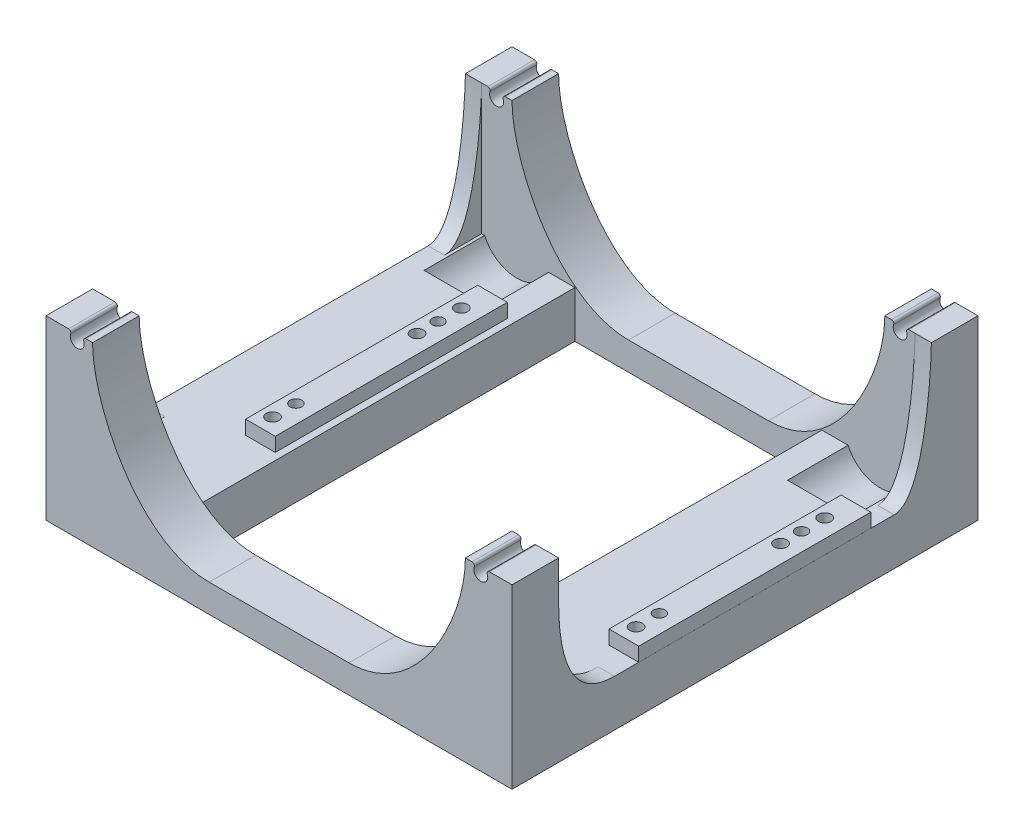
SolidWorks part; units mm, degrees
other "标注1"
sketch "草图19" plane through (-50, 38.0005, 50) normal (-0.1688, 0.677, 0.7163) x (0.9244, -0.1433, 0.3534)
ref_plane "前视基准面" through (0, 0, 0) normal (0, 0, 1) x (1, 0, 0)
ref_plane "上视基准面" through (0, 0, 0) normal (0, 1, 0) x (1, 0, 0)
ref_plane "右视基准面" through (0, 0, 0) normal (1, 0, 0) x (0, 0, -1)
sketch "草图1" plane through (0, 0, 0) normal (0, 1, 0) x (1, 0, 0)
  line L1 (-50, 50) -> (50, 50)
  line L2 (-50, 50) -> (-50, -50)
  line L3 (-50, -50) -> (50, -50)
  line L4 (50, 50) -> (50, -50)
  line L5 (-50, 50) -> (50, -50) construction
  line L6 (-50, -50) -> (50, 50) construction
  point P0 (0, 0)
  dimension "D1" = 100
  dimension "D2" = 100
extrude "凸台-拉伸1" add sketch "草图1" along normal blind 3
sketch "草图2" plane through (0, 3, 0) normal (0, 1, 0) x (1, 0, 0)
  line L1 (0, 0) -> (0, 7.7129) construction
  line L2 (0, 0) -> (13.0975, 0) construction
  line L3 (40, 50) -> (40, 40)
  line L4 (-50, 50) -> (-40, 50)
  line L5 (-50, 50) -> (-50, 40)
  line L6 (-50, 40) -> (-40, 40)
  line L7 (-40, 50) -> (-40, 40)
  line L8 (50, 40) -> (40, 40)
  line L9 (50, 50) -> (50, 40)
  line L10 (50, 50) -> (40, 50)
  line L11 (50, -50) -> (40, -50)
  line L12 (50, -50) -> (50, -40)
  line L13 (50, -40) -> (40, -40)
  line L14 (-40, -50) -> (-40, -40)
  line L15 (-50, -40) -> (-40, -40)
  line L16 (-50, -50) -> (-50, -40)
  line L17 (-50, -50) -> (-40, -50)
  line L18 (40, -50) -> (40, -40)
  dimension "D2" = 10
  dimension "D3" = 10
extrude "凸台-拉伸2" add sketch "草图2" along normal blind 35
sketch "草图4" plane through (0, 38, 0) normal (0, 1, 0) x (1, 0, 0)
  line L0 (0, 0) -> (0, 4.7168) construction
  line L1 (0, 0) -> (6.2704, 0) construction
  line L2 (-43.3, 45) -> (43.3, 45)
  line L3 (-40, 40) -> (-40, 50) construction
  point P3 (0, 45)
  point P9 (-40, 45)
  dimension "D1" = 86.6
sketch "草图5" plane through (0, 0, -50) normal (0, 0, -1) x (-1, 0, 0)
  line L0 (-43.3, 36.8) -> (43.3, 36.8) construction
  line L1 (0, 0) -> (0, 16.0032) construction
  line L2 (-50, 38) -> (-40, 38) construction
  circle A0 centre (-43.3, 36.8) radius 1.5
  circle A1 centre (43.3, 36.8) radius 1.5
  point P5 (0, 36.8)
  dimension "D2" = 3
  dimension "D1" = 86.6
  dimension "D3" = 1.2
extrude "切除-拉伸2" cut sketch "草图5" against normal up to surface (100 mm away) contours A1 | A0
fillet "圆角1" radius 0.5 8 edges at (-44.2, 38, 45) (-42.4, 38, 45) (44.2, 38, 45) (42.4, 38, 45) (44.2, 38, -45) (42.4, 38, -45) (-44.2, 38, -45) (-42.4, 38, -45)
sketch "草图7" plane through (0, 3, 0) normal (0, 1, 0) x (1, 0, 0)
  line L1 (-40, 50) -> (40, 50)
  line L2 (-40, 50) -> (-40, 40)
  line L3 (-40, 40) -> (40, 40)
  line L4 (40, 50) -> (40, 40)
  line L5 (-40, -40) -> (40, -40)
  line L6 (-40, -40) -> (-40, -50)
  line L7 (-40, -50) -> (40, -50)
  line L8 (40, -40) -> (40, -50)
  line M2 (-40, -40) -> (-40, -50)
  line M3 (-40, -50) -> (40, -50)
  line M4 (40, -50) -> (40, -40)
  line M8 (40, 40) -> (40, 50)
  line M9 (40, 50) -> (-40, 50)
  line M10 (-40, 50) -> (-40, 40)
extrude "凸台-拉伸3" add sketch "草图7" along normal blind 3 contours L5 M2 M3 M4 | L3 M10 M8 M9
sketch "草图8" plane through (0, 0, 50) normal (0, 0, 1) x (1, 0, 0)
  line L1 (-40, 38) -> (-40, 6) construction
  line L2 (0, 0) -> (0, 19.6517) construction
  line L3 (-50, 0) -> (50, 0) construction
  line L4 (-40, 38) -> (-40, 6)
  line L5 (-40, 6) -> (-15, 6)
  line L6 (40, 6) -> (15, 6)
  line L7 (40, 38) -> (40, 6)
  line L8 (-40, 6) -> (40, 6) construction
  spline S0 degree 3 poles (-40, 38) (-40, 26.4936) (-30.1503, 6) (-15, 6) knots 0 0 0 0 1 1 1 1
  spline S1 degree 3 poles (40, 38) (40, 26.4936) (30.1503, 6) (15, 6) knots 0 0 0 0 1 1 1 1
  dimension "D1" = 25
extrude "凸台-拉伸4" add sketch "草图8" against normal up to surface (10 mm away) up to face at (0, 29.2338, 40)
sketch "草图9" plane through (0, 0, -50) normal (0, 0, -1) x (-1, 0, 0)
  line L2 (-40, 6) -> (-15, 6)
  line L3 (-40, 38) -> (-40, 6)
  line L4 (-40, 6) -> (-15, 6)
  line L5 (-40, 38) -> (-40, 6)
  line L6 (40, 6) -> (40, 38)
  line L7 (15, 6) -> (40, 6)
  line L8 (40, 6) -> (40, 38)
  line L9 (15, 6) -> (40, 6)
  spline S1 degree 3 poles (144.0222, 1994.8743) (169.4851, -2146.6398) (-527.9806, 2160.2859) (637.2814, -1841.186) knots -3.481249 -3.481249 -3.481249 -3.481249 4.802323 4.802323 4.802323 4.802323 only from (-15, 6) to (-40, 38)
  spline S2 degree 3 poles (-15, 6) (-30.1503, 6) (-40, 26.4936) (-40, 38) knots 0 0 0 0 1 1 1 1
  spline S3 degree 3 poles (-637.2972, -1841.2401) (527.993, 2160.3455) (-169.4925, -2146.7034) (-144.0219, 1994.9391) knots -3.80236 -3.80236 -3.80236 -3.80236 4.481293 4.481293 4.481293 4.481293 only from (40, 38) to (15, 6)
  spline S4 degree 3 poles (40, 38) (40, 26.4936) (30.1503, 6) (15, 6) knots 0 0 0 0 1 1 1 1
  dimension "D1" = 0
  dimension "D2" = 0
extrude "凸台-拉伸5" add sketch "草图9" against normal up to surface (10 mm away) up to face at (0, 29.2338, -40)
sketch "草图13" plane through (0, 3, 0) normal (0, 1, 0) x (1, 0, 0)
  line L0 (-15, -40) -> (-40, -40) construction
  line L1 (-50, 40) -> (-26.5, 40)
  line L2 (-50, 40) -> (-50, -40)
  line L3 (-50, -40) -> (-26.5, -40)
  line L4 (-26.5, 40) -> (-26.5, -40)
  line L5 (0, 0) -> (0, 12.4969) construction
  line L6 (26.5, 40) -> (26.5, -40)
  line L7 (50, -40) -> (26.5, -40)
  line L8 (50, 40) -> (50, -40)
  line L9 (50, 40) -> (26.5, 40)
  dimension "D1" = 23.5
extrude "凸台-拉伸6" add sketch "草图13" along normal blind 7
sketch "草图17" plane through (50, 0, 0) normal (1, 0, 0) x (0, 0, -1)
  line L0 (-40, 10) -> (40, 10) construction
  line L1 (40, 38) -> (40, 10) construction
  line L2 (32, 10) -> (40, 10)
  line L3 (40, 10) -> (40, 38)
  line L4 (-40, 38) -> (-40, 10) construction
  line L6 (-40, 30) -> (-40, 10)
  line L7 (-40, 10) -> (-28, 10)
  spline S0 degree 3 poles (40, 38) (40, 35.1023) (38.9761, 10) (32, 10) knots 0 0 0 0 1 1 1 1
  spline S1 degree 2 poles (-40, 30) (-40, 10) (-28, 10) knots 0 0 0 1 1 1
  point P11 (37.8859, 23.9283)
  point P14 (37.9112, 24.8759)
  point P19 (0, 0)
  point P20 (38.8248, 24.2084)
  dimension "D1" = 8
  dimension "D2" = 12
  dimension "D3" = 20
extrude "凸台-拉伸8" add sketch "草图17" against normal blind 3.5
sketch "草图18" plane through (-50, 0, 0) normal (-1, 0, 0) x (0, 0, 1)
  line L2 (40, 10) -> (40, 30)
  line L3 (28, 10) -> (40, 10)
  line L4 (40, 10) -> (40, 30)
  line L5 (28, 10) -> (40, 10)
  line L6 (-40, 10) -> (-32, 10)
  line L7 (-40, 38) -> (-40, 10)
  line L8 (-40, 10) -> (-32, 10)
  line L9 (-40, 38) -> (-40, 10)
  parabola Q1 (40, 30) -> (28, 10) focus (31.1765, 15.2941) apex (33.5121, 11.4014)
  parabola Q2 (40, 30) -> (28, 10) focus (31.1765, 15.2941) apex (33.5121, 11.4014)
  spline S1 degree 3 poles (326.3572, 1976.9584) (-292.9927, -2127.0588) (132.3966, 2186.1852) (-155.4921, -1958.5179) knots -3.006877 -3.006877 -3.006877 -3.006877 4.085231 4.085231 4.085231 4.085231 only from (-32, 10) to (-40, 38)
  spline S2 degree 3 poles (-32, 10) (-38.9761, 10) (-40, 35.1023) (-40, 38) knots 0 0 0 0 1 1 1 1
  dimension "D1" = 0
  dimension "D2" = 0
extrude "凸台-拉伸9" add sketch "草图18" against normal blind 3.5
sketch "草图12" plane through (0, 0, -40) normal (0, 0, 1) x (1, 0, 0)
  line L0 (-50, 38) -> (-50, 0) construction
  line L3 (0, 0) -> (0, 12.4127) construction
  line L4 (-26.5, 10) -> (-46.5, 10) construction
  circle A0 centre (-39, 13) radius 7.5
  circle A1 centre (39, 13) radius 7.5
  dimension "D1" = 15
  dimension "D2" = 3
  dimension "D3" = 11
extrude "切除-拉伸3" cut sketch "草图12" along normal blind 13
sketch "草图14" plane through (0, 10, 0) normal (0, 1, 0) x (1, 0, 0)
  line L0 (-45.8739, 27) -> (-45.8739, 40) construction
  line L1 (-34.3739, 27) -> (-28.0039, 27)
  line L2 (-34.3739, 27) -> (-34.3739, -22.8)
  line L3 (-34.3739, -22.8) -> (-28.0039, -22.8)
  line L4 (-28.0039, 27) -> (-28.0039, -22.8)
  line L7 (-45.8739, 27) -> (-32.1261, 27) construction
  line L8 (0, 0) -> (0, 13.2318) construction
  line L9 (-31.8739, 27) -> (-31.8739, -22.8) construction
  line L10 (43.6261, 27) -> (49.9961, 27)
  line L11 (43.6261, 27) -> (43.6261, -22.8)
  line L12 (43.6261, -22.8) -> (49.9961, -22.8)
  line L13 (49.9961, 27) -> (49.9961, -22.8)
  line L14 (46.1261, 27) -> (46.1261, -22.8) construction
  circle A0 centre (-31.8739, 21) radius 1.35
  circle A1 centre (-31.8739, 16) radius 1.25
  circle A2 centre (-31.8739, 11.5) radius 1.35
  circle A3 centre (-31.8739, -14.5) radius 1.25
  circle A4 centre (-31.8739, -19.5) radius 1.35
  circle A5 centre (46.1261, 21) radius 1.35
  circle A6 centre (46.1261, 16) radius 1.25
  circle A7 centre (46.1261, 11.5) radius 1.35
  circle A8 centre (46.1261, -14.5) radius 1.25
  circle A9 centre (46.1261, -19.5) radius 1.35
  dimension "D2" = 2.7
  dimension "D3" = 2.5
  dimension "D4" = 2.7
  dimension "D5" = 2.5
  dimension "D6" = 2.7
  dimension "D1" = 11.5
  dimension "D7" = 6
  dimension "D8" = 2.5
  dimension "D9" = 9.5
  dimension "D10" = 4.5
  dimension "D11" = 31
  dimension "D12" = 5
  dimension "D13" = 2
  dimension "D14" = 3.87
  dimension "D15" = 3.3
extrude "凸台-拉伸7" add sketch "草图14" along normal blind 3
sketch "草图3" plane through (0, 3, 0) normal (0, 1, 0) x (1, 0, 0)
  line L5 (-26.5, 40) -> (26.5, 40)
  line L6 (-26.5, 40) -> (-26.5, -40)
  line L7 (-26.5, -40) -> (26.5, -40)
  line L8 (26.5, 40) -> (26.5, -40)
  point P0 (0, 0)
extrude "切除-拉伸1" cut sketch "草图3" against normal up to surface (3 mm away) up to face at (0, 0, 0)
equation "\"m\"= 2"
